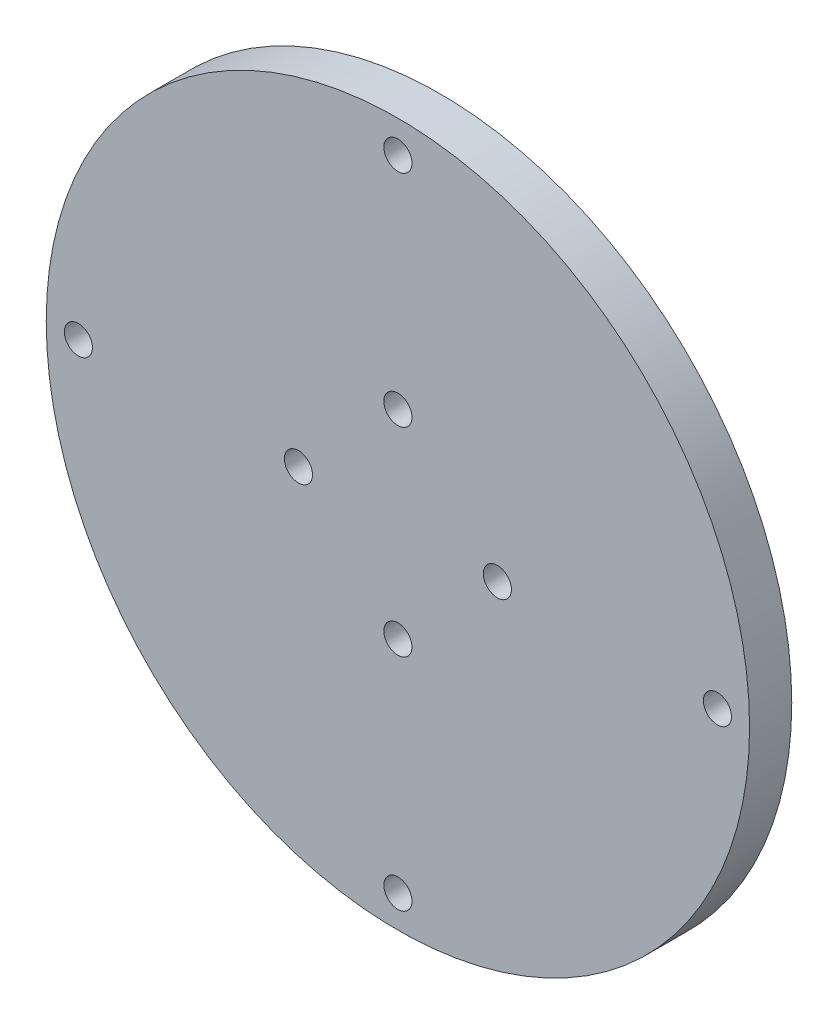
SolidWorks part; units mm, degrees
material "1060 Alloy"
ref_plane "Front Plane" through (0, 0, 0) normal (0, 0, 1) x (1, 0, 0)
ref_plane "Top Plane" through (0, 0, 0) normal (0, 1, 0) x (1, 0, 0)
ref_plane "Right Plane" through (0, 0, 0) normal (1, 0, 0) x (0, 0, -1)
sketch "Sketch1" plane through (0, 0, 0) normal (0, 0, 1) x (1, 0, 0)
  line L0 (-25, 0) -> (25, 0) construction
  line L5 (0, 25) -> (0, -25) construction
  line L6 (-7.0711, 0) -> (0, 7.0711) construction
  line L7 (0, 7.0711) -> (7.0711, 0) construction
  line L8 (7.0711, 0) -> (0, -7.0711) construction
  line L9 (0, -7.0711) -> (-7.0711, 0) construction
  circle A0 centre (0, 0) radius 25
  circle A9 centre (0, 0) radius 22.715
  circle A10 centre (0, 22.715) radius 1
  circle A11 centre (0, 7.0711) radius 1
  circle A12 centre (7.0711, 0) radius 1
  circle A13 centre (0, -7.0711) radius 1
  circle A14 centre (-7.0711, 0) radius 1
  circle A16 centre (22.715, 0) radius 1
  circle A17 centre (0, -22.715) radius 1
  circle A18 centre (-22.715, 0) radius 1
  point P5 (0, 25)
  point P16 (0, -25)
  dimension "D1" = 50
  dimension "D2" = 45.43
  dimension "D8" = 10
  dimension "D9" = 2
  dimension "D10" = 2
  dimension "D11" = 2
  dimension "D12" = 2
  dimension "D3" = 2
  dimension "D4" = 2
  dimension "D5" = 2
  dimension "D13" = 2
  dimension "D6" = 90
  dimension "D7" = 90
extrude "Boss-Extrude1" add sketch "Sketch1" along normal mid plane 3
